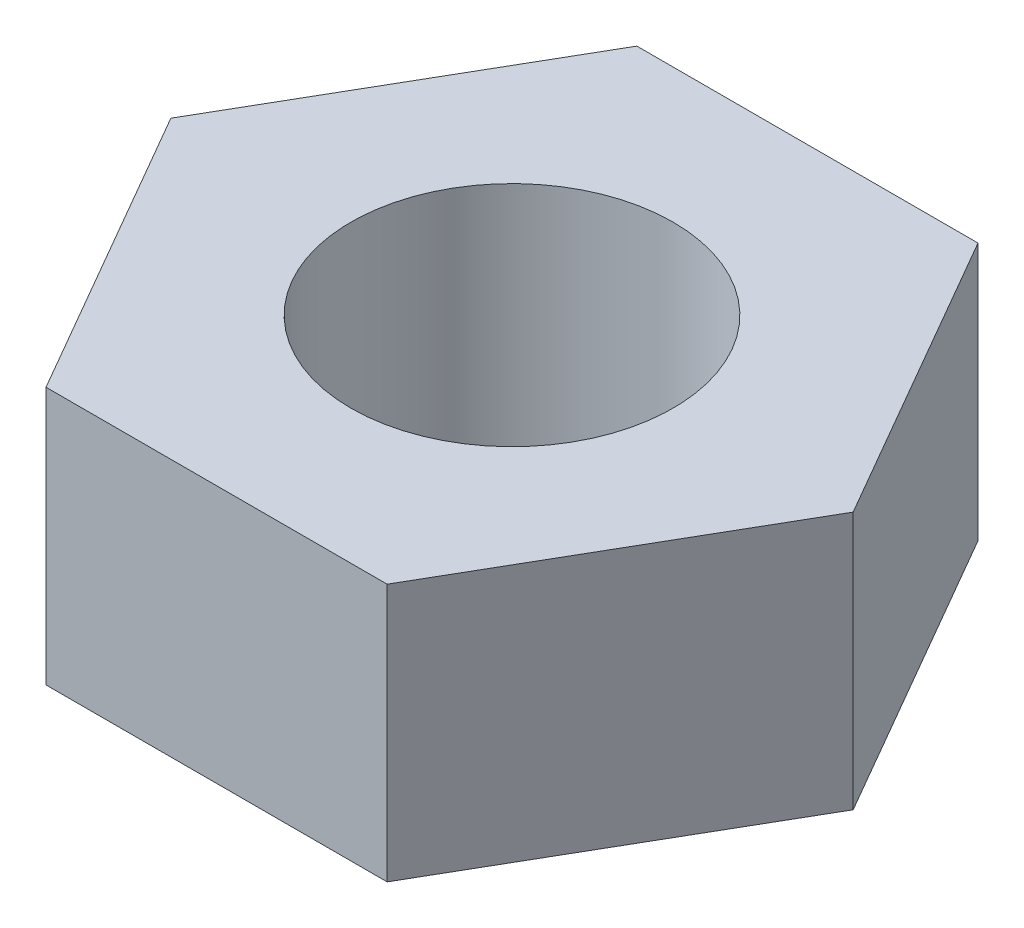
SolidWorks part; units mm, degrees
ref_plane "前视基准面" through (0, 0, 0) normal (0, 0, 1) x (1, 0, 0)
ref_plane "上视基准面" through (0, 0, 0) normal (0, 1, 0) x (1, 0, 0)
ref_plane "右视基准面" through (0, 0, 0) normal (1, 0, 0) x (0, 0, -1)
sketch "草图1" plane through (0, 0, 0) normal (0, 1, 0) x (1, 0, 0)
  line L1 (3.1754, 0) -> (1.5877, 2.75)
  line L2 (1.5877, 2.75) -> (-1.5877, 2.75)
  line L3 (-1.5877, 2.75) -> (-3.1754, 0)
  line L4 (-3.1754, 0) -> (-1.5877, -2.75)
  line L5 (-1.5877, -2.75) -> (1.5877, -2.75)
  line L6 (1.5877, -2.75) -> (3.1754, 0)
  circle A0 centre (0, 0) radius 1.5
  circle A1 centre (0, 0) radius 2.75 construction
  dimension "D1" = 3
  dimension "D2" = 5.5
extrude "凸台-拉伸1" add sketch "草图1" along normal blind 2.4
